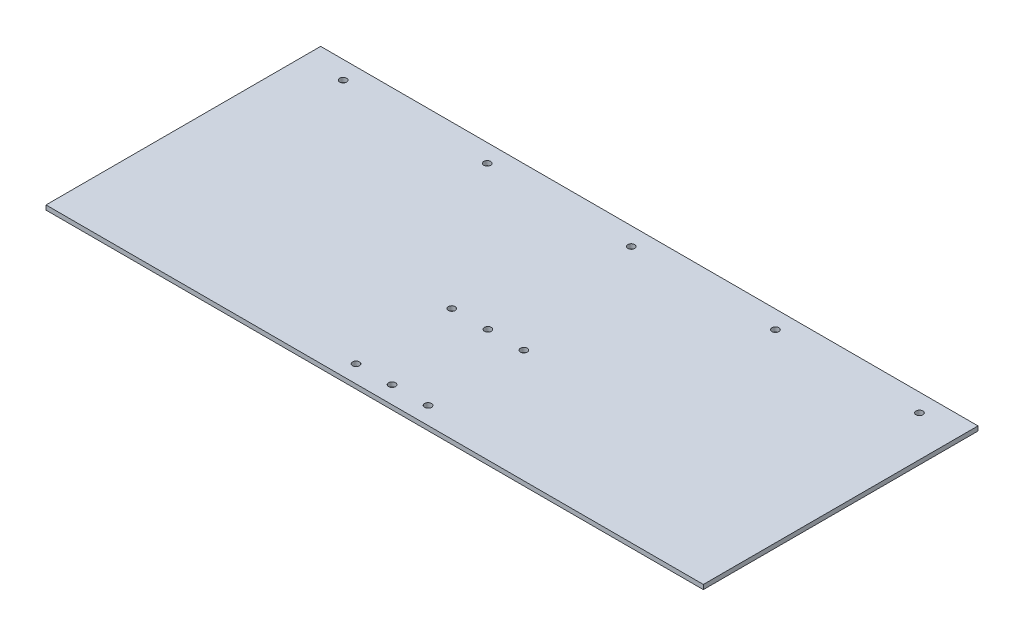
SolidWorks part; units mm, degrees
material "5052-H32"
ref_plane "Front" through (0, 0, 0) normal (0, 0, 1) x (1, 0, 0)
ref_plane "Top" through (0, 0, 0) normal (0, 1, 0) x (1, 0, 0)
ref_plane "Right" through (0, 0, 0) normal (1, 0, 0) x (0, 0, -1)
sketch "Sketch1" plane through (0, 0, 0) normal (0, 1, 0) x (1, 0, 0)
  line L0 (231.775, 0) -> (231.775, 46.0375) construction
  line L1 (0, 0) -> (463.55, 0)
  line L2 (0, 0) -> (0, 193.675)
  line L3 (0, 193.675) -> (463.55, 193.675)
  line L4 (463.55, 0) -> (463.55, 193.675)
  line L5 (231.775, 46.0375) -> (253.2062, 46.0375) construction
  line L6 (206.375, 12.2555) -> (257.175, 12.2555) construction
  line L7 (206.375, 79.8195) -> (257.175, 79.8195) construction
  line L8 (231.775, 193.675) -> (231.775, 180.975) construction
  circle A0 centre (231.775, 46.0375) radius 21.4312 construction
  circle A1 centre (231.775, 12.2555) radius 2.4257
  circle A2 centre (257.175, 12.2555) radius 2.4257
  circle A3 centre (206.375, 12.2555) radius 2.4257
  circle A4 centre (257.175, 79.8195) radius 2.4257
  circle A5 centre (231.775, 79.8195) radius 2.4257
  circle A6 centre (206.375, 79.8195) radius 2.4257
  circle A7 centre (231.775, 180.975) radius 2.4257
  circle A8 centre (333.375, 180.975) radius 2.4257
  circle A9 centre (434.975, 180.975) radius 2.4257
  circle A12 centre (28.575, 180.975) radius 2.4257
  circle A13 centre (130.175, 180.975) radius 2.4257
  dimension "D3" = 42.8625
  dimension "D5" = 4.8514
  dimension "D9" = 4.8514
  dimension "D1" = 463.55
  dimension "D2" = 193.675
  dimension "D4" = 46.0375
  dimension "D6" = 33.782
  dimension "D7" = 25.4
  dimension "D8" = 12.7
  dimension "D11" = 101.6
  dimension "D10" = 3
extrude "Boss-Extrude1" add sketch "Sketch1" along normal blind 3.175
sketch "Sketch2" plane through (0, 3.175, 0) normal (0, 1, 0) x (1, 0, 0)
  line L0 (0, 193.675) -> (0, 0) construction
  line L1 (0, 0) -> (463.55, 0) construction
  line L2 (231.775, 193.675) -> (231.775, -51.395) construction
  line L3 (463.55, 193.675) -> (0, 193.675) construction
  circle A0 centre (6.35, 12.7) radius 2.4257
  circle A1 centre (6.35, 82.55) radius 2.4257
  circle A2 centre (6.35, 152.4) radius 2.4257
  circle A3 centre (6.35, 222.25) radius 2.4257
  circle A4 centre (457.2, 222.25) radius 2.4257
  circle A5 centre (457.2, 152.4) radius 2.4257
  circle A6 centre (457.2, 82.55) radius 2.4257
  circle A7 centre (457.2, 12.7) radius 2.4257
  dimension "D3" = 4.8514
  dimension "D1" = 6.35
  dimension "D2" = 12.7
  dimension "D5" = 69.85
  dimension "D4" = 4
extrude "Cut-Extrude1" [suppressed] cut sketch "Sketch2" against normal through all
fillet "Fillet1" [suppressed] radius 3.175
